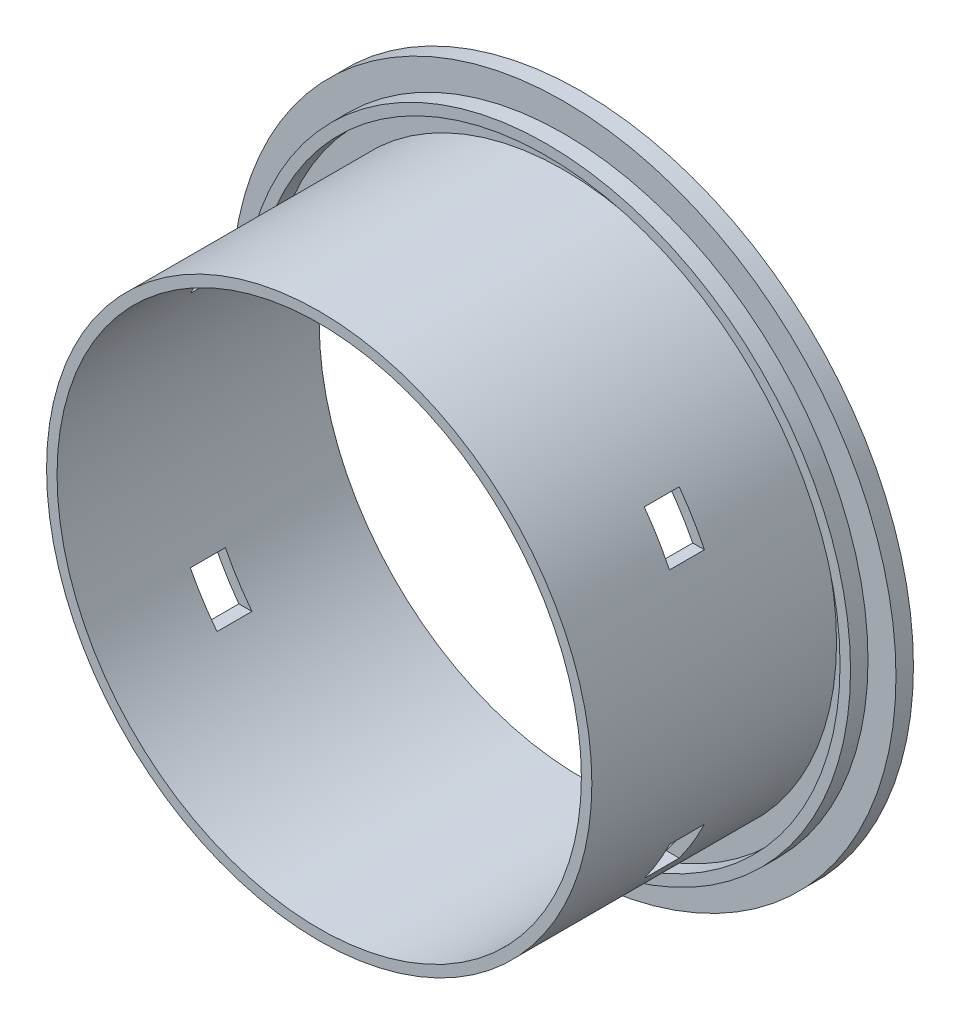
SolidWorks part; units mm, degrees
ref_plane "Front Plane" through (0, 0, 0) normal (0, 0, 1) x (1, 0, 0)
ref_plane "Top Plane" through (0, 0, 0) normal (0, 1, 0) x (1, 0, 0)
ref_plane "Right Plane" through (0, 0, 0) normal (1, 0, 0) x (0, 0, -1)
sketch "Sketch2" plane through (0, 0, 0) normal (0, 0, 1) x (1, 0, 0)
  circle A0 centre (0, 0) radius 95
  circle A1 centre (0, 0) radius 75
  dimension "D1" = 190
  dimension "D2" = 150
  dimension "D3" = 20
extrude "Boss-Extrude1" add sketch "Sketch2" along normal blind 5
sketch "Sketch3" plane through (0, 0, 0) normal (0, 0, 1) x (1, 0, 0)
  circle A0 centre (0, 0) radius 87
  circle A1 centre (0, 0) radius 95 construction
  circle A2 centre (0, 0) radius 84
  dimension "D1" = 8
  dimension "D2" = 3
extrude "Boss-Extrude2" add sketch "Sketch3" along normal blind 10
sketch "Sketch4" plane through (0, 0, 5) normal (0, 0, 1) x (1, 0, 0)
  circle A0 centre (0, 0) radius 75
  circle A1 centre (0, 0) radius 78
  dimension "D1" = 3
extrude "Boss-Extrude3" add sketch "Sketch4" along normal blind 70
sketch "Sketch5" plane through (0, 0, 0) normal (0, 0, 1) x (1, 0, 0)
  line L0 (0, 102.8311) -> (0, -104.5953) construction
  line L1 (-104.5953, 0) -> (100.8148, -2.2683) construction
ref_plane "Plane1" through (10, 0, 0) normal (1, 0, 0) x (0, 0, -1)
sketch "Sketch6" plane through (10, 0, 0) normal (1, 0, 0) x (0, 0, -1)
  line L1 (-45, 46) -> (-35, 46)
  line L2 (-45, 46) -> (-45, 34)
  line L3 (-45, 34) -> (-35, 34)
  line L4 (-35, 46) -> (-35, 34)
  line L5 (-45, 46) -> (-35, 34) construction
  line L6 (-45, 34) -> (-35, 46) construction
  point P0 (-40, 40)
  point P5 (0, 0)
  point P6 (0, 0)
  point P7 (0, 0)
  point P8 (0, 0)
  point P9 (0, 0)
  dimension "D1" = 10
  dimension "D2" = 12
extrude "Cut-Extrude3" cut sketch "Sketch6" against normal through all both and the other way through all
sketch "Sketch7" plane through (10, 0, 0) normal (1, 0, 0) x (0, 0, -1)
  line L1 (-45, -34) -> (-35, -34)
  line L2 (-45, -34) -> (-45, -46)
  line L3 (-45, -46) -> (-35, -46)
  line L4 (-35, -34) -> (-35, -46)
  line L5 (-45, -34) -> (-35, -46) construction
  line L6 (-45, -46) -> (-35, -34) construction
  point P0 (-40, -40)
  dimension "D1" = 10
  dimension "D2" = 12
extrude "Cut-Extrude4" cut sketch "Sketch7" against normal through all both and the other way through all
